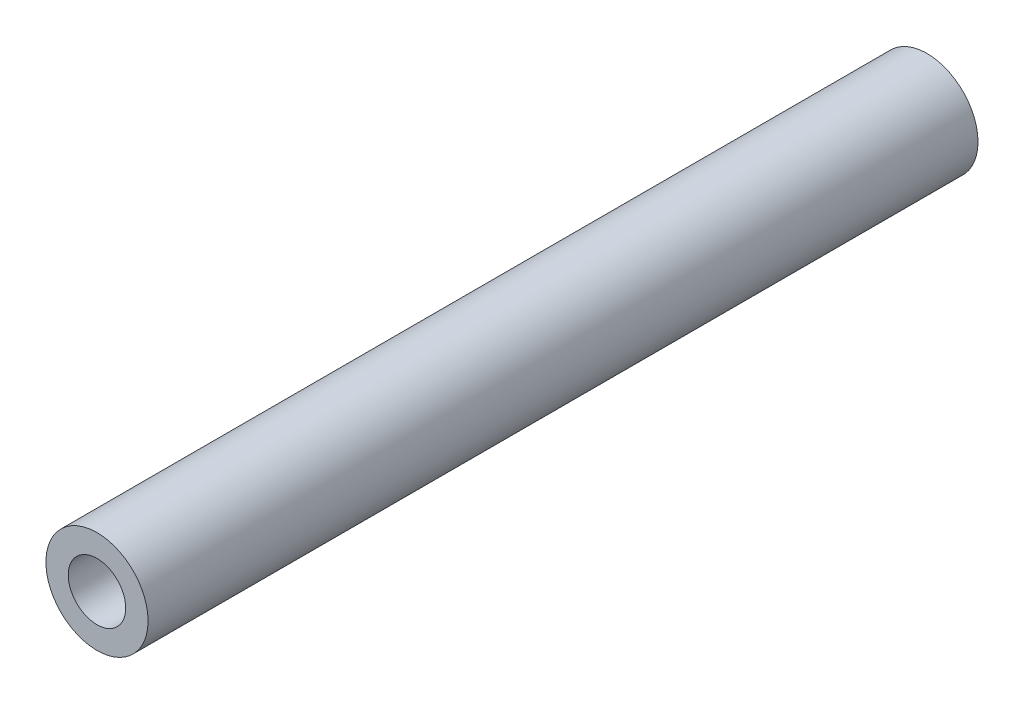
SolidWorks part; units mm, degrees
ref_plane "Спереди" through (0, 0, 0) normal (0, 0, 1) x (1, 0, 0)
ref_plane "Сверху" through (0, 0, 0) normal (0, 1, 0) x (1, 0, 0)
ref_plane "Справа" through (0, 0, 0) normal (1, 0, 0) x (0, 0, -1)
sketch "Эскиз1" plane through (0, 0, 0) normal (0, 0, 1) x (1, 0, 0)
  circle A0 centre (0, 0) radius 4
  circle A1 centre (0, 0) radius 2.25
extrude "Tie_tube" add sketch "Эскиз1" along normal blind 65 from offset 32
